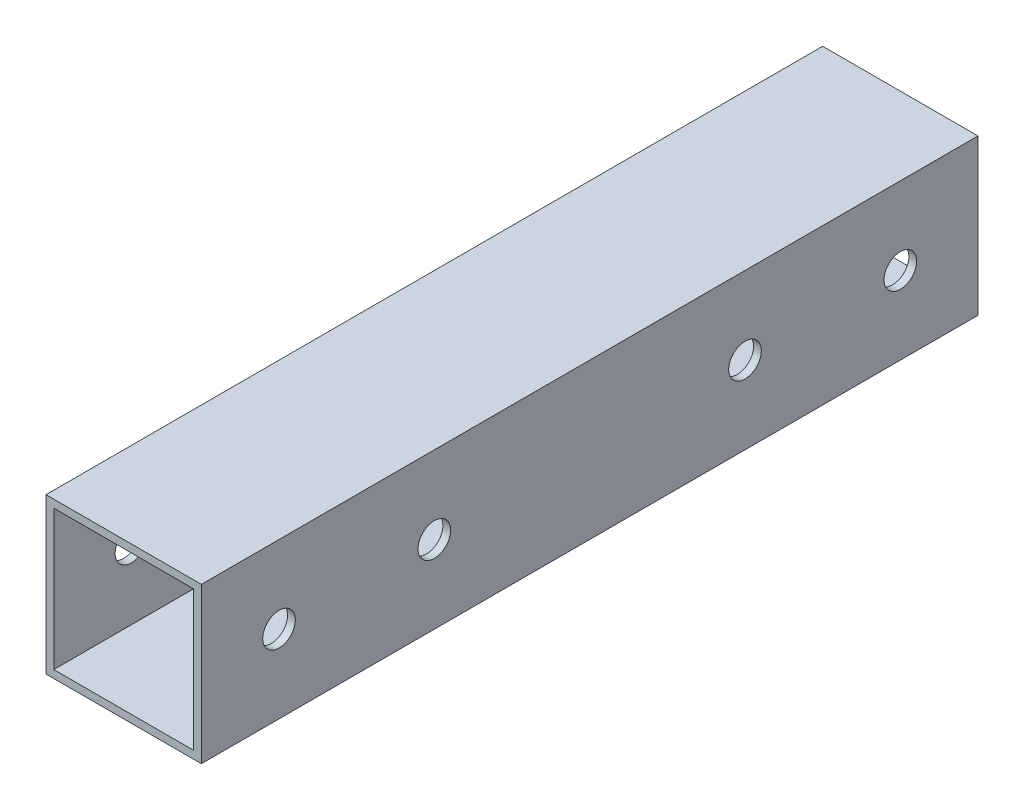
SolidWorks part; units mm, degrees
ref_plane "前视基准面" through (0, 0, 0) normal (0, 0, 1) x (1, 0, 0)
ref_plane "上视基准面" through (0, 0, 0) normal (0, 1, 0) x (1, 0, 0)
ref_plane "右视基准面" through (0, 0, 0) normal (1, 0, 0) x (0, 0, -1)
sketch "草图1" plane through (0, 0, 0) normal (0, 0, 1) x (1, 0, 0)
  line L1 (-10, 10) -> (10, 10)
  line L2 (-10, 10) -> (-10, -10)
  line L3 (-10, -10) -> (10, -10)
  line L4 (10, 10) -> (10, -10)
  line L5 (-10, 10) -> (10, -10) construction
  line L6 (-10, -10) -> (10, 10) construction
  point P0 (0, 0)
  dimension "D1" = 20
  dimension "D2" = 20
extrude "凸台-拉伸1" add sketch "草图1" along normal blind 100
sketch "草图2" plane through (10, 0, 0) normal (1, 0, 0) x (0, 0, -1)
  line L0 (-50, 10) -> (-50, -10) construction
  line L1 (-100, 10) -> (0, 10) construction
  line L2 (-100, -10) -> (0, -10) construction
  line L3 (0, -10) -> (0, 10) construction
  circle A0 centre (-10, 0) radius 2.1
  circle A1 centre (-30, 0) radius 2.1
  circle A2 centre (-90, 0) radius 2.1
  circle A3 centre (-70, 0) radius 2.1
  dimension "D1" = 10
  dimension "D3" = 4.2
  dimension "D5" = 20
  dimension "D2" = 10
  dimension "D4" = 2
extrude "切除-拉伸1" cut sketch "草图2" against normal through all
sketch "草图3" plane through (0, -10, 0) normal (0, -1, 0) x (1, 0, 0)
  line L1 (-10, 100) -> (10, 100) construction
  line L2 (10, 100) -> (10, 0) construction
  circle A0 centre (0, 90) radius 2.1
  circle A1 centre (0, 70) radius 2.1
  dimension "D1" = 4.2
  dimension "D2" = 4.2
  dimension "D3" = 20
  dimension "D4" = 10
  dimension "D5" = 10
sketch "草图4" plane through (0, 0, 0) normal (0, 0, -1) x (-1, 0, 0)
  line L1 (-9, 9) -> (9, 9)
  line L2 (-9, 9) -> (-9, -9)
  line L3 (-9, -9) -> (9, -9)
  line L4 (9, 9) -> (9, -9)
  line L5 (-9, 9) -> (9, -9) construction
  line L6 (-9, -9) -> (9, 9) construction
  point P0 (0, 0)
  dimension "D1" = 18
  dimension "D2" = 18
extrude "切除-拉伸2" cut sketch "草图4" against normal through all
